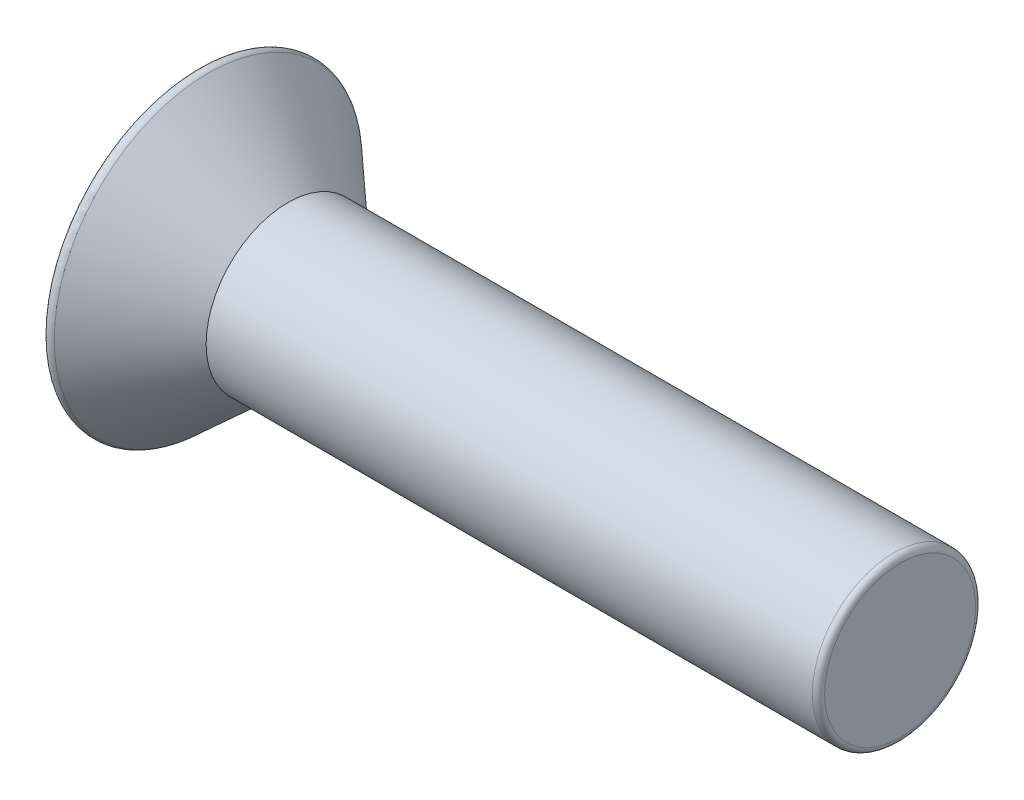
SolidWorks part; units mm, degrees
material "1.0044 (S275JR)"
ref_plane "Ön Düzlem" through (0, 0, 0) normal (0, 0, 1) x (1, 0, 0)
ref_plane "Üst Düzlem" through (0, 0, 0) normal (0, 1, 0) x (1, 0, 0)
ref_plane "Sağ Düzlem" through (0, 0, 0) normal (1, 0, 0) x (0, 0, -1)
sketch "Çizim1" plane through (0, 0, 0) normal (0, 0, 1) x (1, 0, 0)
  line L0 (0, 0) -> (0, 4)
  line L1 (0, 4) -> (-30, 4)
  line L2 (-30, 4) -> (-34.4, 8)
  line L3 (-34.4, 8) -> (-34.4, 0)
  line L4 (-34.4, 0) -> (0, 0)
  dimension "D1" = 4
  dimension "D2" = 30
  dimension "D3" = 8
  dimension "D4" = 4.4
revolve "Döndür1" add sketch "Çizim1" angle 360 about L4
cosmetic thread "Kozmetik Diş Açma1" parameters "D2"=6.619
sketch "Çizim2" plane through (-34.4, 0, 0) normal (-1, 0, 0) x (0, 0, 1)
  line L1 (2.8868, 0) -> (1.4434, 2.5)
  line L2 (1.4434, 2.5) -> (-1.4434, 2.5)
  line L3 (-1.4434, 2.5) -> (-2.8868, 0)
  line L4 (-2.8868, 0) -> (-1.4434, -2.5)
  line L5 (-1.4434, -2.5) -> (1.4434, -2.5)
  line L6 (1.4434, -2.5) -> (2.8868, 0)
  circle A0 centre (0, 0) radius 2.5 construction
  dimension "D1" = 5
extrude "Kes-Ekstrüzyon1" cut sketch "Çizim2" against normal blind 5
fillet "Radyus2" radius 0.3 2 edges at (0, 0, 4) (-34.4, 0, 8)
